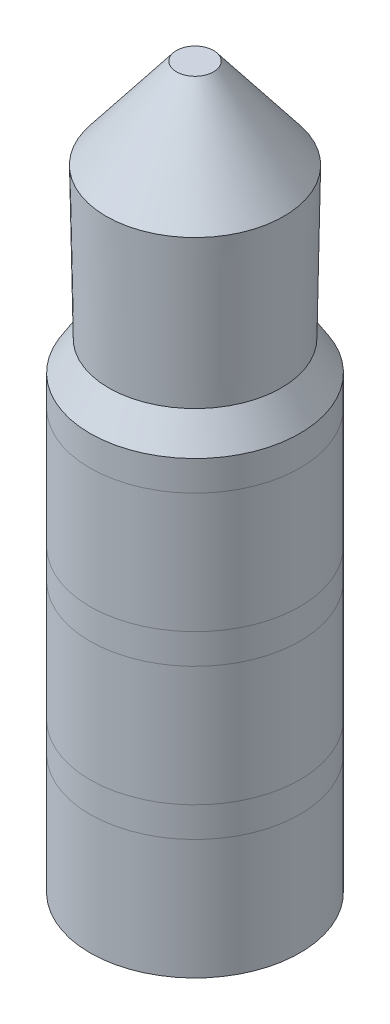
SolidWorks part; units mm, degrees
ref_plane "Front Plane" through (0, 0, 0) normal (0, 0, 1) x (1, 0, 0)
ref_plane "Top Plane" through (0, 0, 0) normal (0, 1, 0) x (1, 0, 0)
ref_plane "Right Plane" through (0, 0, 0) normal (1, 0, 0) x (0, 0, -1)
sketch "Sketch1" plane through (0, 0, 0) normal (0, 1, 0) x (1, 0, 0)
  circle A0 centre (0, 0) radius 1.75
  dimension "D1" = 3.5
extrude "Boss-Extrude1" add sketch "Sketch1" along normal blind 2
sketch "Sketch2" plane through (0, 2, 0) normal (0, 1, 0) x (1, 0, 0)
  circle A0 centre (0, 0) radius 1.75 construction
  circle A1 centre (0, 0) radius 1.75
extrude "Boss-Extrude2" add sketch "Sketch2" along normal blind 0.5 separate body
sketch "Sketch3" plane through (0, 2.5, 0) normal (0, 1, 0) x (1, 0, 0)
  circle A1 centre (0, 0) radius 1.75
  circle A2 centre (0, 0) radius 1.75
  dimension "D1" = 0
extrude "Boss-Extrude3" add sketch "Sketch3" along normal blind 2 separate body
sketch "Sketch4" plane through (0, 4.5, 0) normal (0, 1, 0) x (1, 0, 0)
  circle A1 centre (0, 0) radius 1.75
  circle A2 centre (0, 0) radius 1.75
  dimension "D1" = 0
extrude "Boss-Extrude4" add sketch "Sketch4" along normal blind 0.5 separate body
sketch "Sketch5" plane through (0, 5, 0) normal (0, 1, 0) x (1, 0, 0)
  circle A1 centre (0, 0) radius 1.75
  circle A2 centre (0, 0) radius 1.75
  dimension "D1" = 0
extrude "Boss-Extrude5" add sketch "Sketch5" along normal blind 2 separate body
sketch "Sketch7" plane through (0, 7, 0) normal (0, 1, 0) x (1, 0, 0)
  circle A0 centre (0, 0) radius 1.75 construction
  circle A1 centre (0, 0) radius 1.75
  dimension "D1" = 0
extrude "Boss-Extrude6" add sketch "Sketch7" along normal blind 0.5 separate body contours A1
sketch "Sketch8" plane through (0, 7.5, 0) normal (0, 1, 0) x (1, 0, 0)
  circle A1 centre (0, 0) radius 1.75
  circle A2 centre (0, 0) radius 1.75
  dimension "D1" = 0
extrude "Boss-Extrude7" add sketch "Sketch8" along normal blind 0.5 draft 32 separate body
sketch "Sketch9" plane through (0, 8, 0) normal (0, 1, 0) x (1, 0, 0)
  circle A1 centre (0, 0) radius 1.4376
  circle A2 centre (0, 0) radius 1.4376
  dimension "D1" = 0
extrude "Boss-Extrude8" add sketch "Sketch9" along normal blind 2.5 draft 1 draft outward yes
sketch "Sketch10" plane through (0, 10.5, 0) normal (0, 1, 0) x (1, 0, 0)
  circle A1 centre (0, 0) radius 1.4812
  circle A2 centre (0, 0) radius 1.4812
  dimension "D1" = 0
extrude "Boss-Extrude9" add sketch "Sketch10" along normal blind 1.5 draft 38
